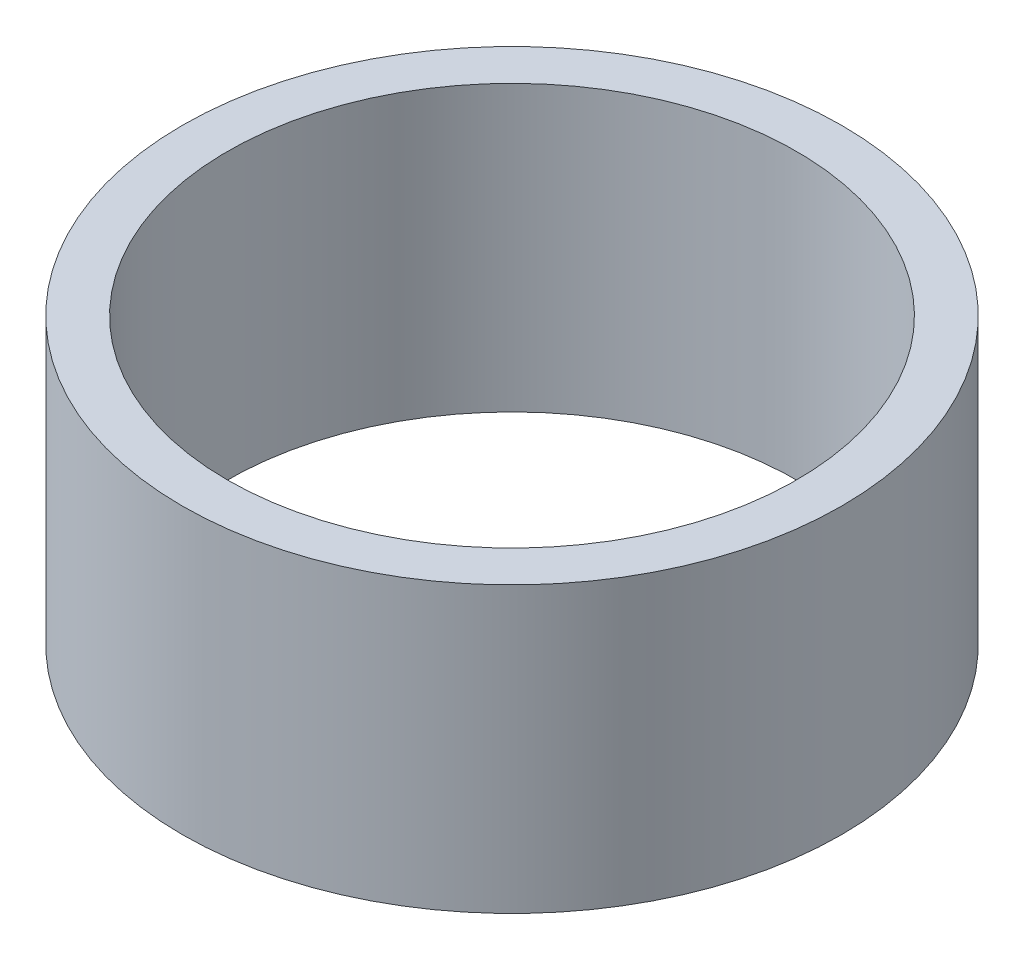
SolidWorks part; units mm, degrees
ref_plane "Front Plane" through (0, 0, 0) normal (0, 0, 1) x (1, 0, 0)
ref_plane "Top Plane" through (0, 0, 0) normal (0, 1, 0) x (1, 0, 0)
ref_plane "Right Plane" through (0, 0, 0) normal (1, 0, 0) x (0, 0, -1)
sketch "Sketch1" plane through (0, 0, 0) normal (0, 1, 0) x (1, 0, 0)
  circle A0 centre (0, 0) radius 4.1
  circle A1 centre (0, 0) radius 4.75
  dimension "D1" = 8.2
  dimension "D2" = 9.5
extrude "Boss-Extrude1" add sketch "Sketch1" along normal blind 4.1
